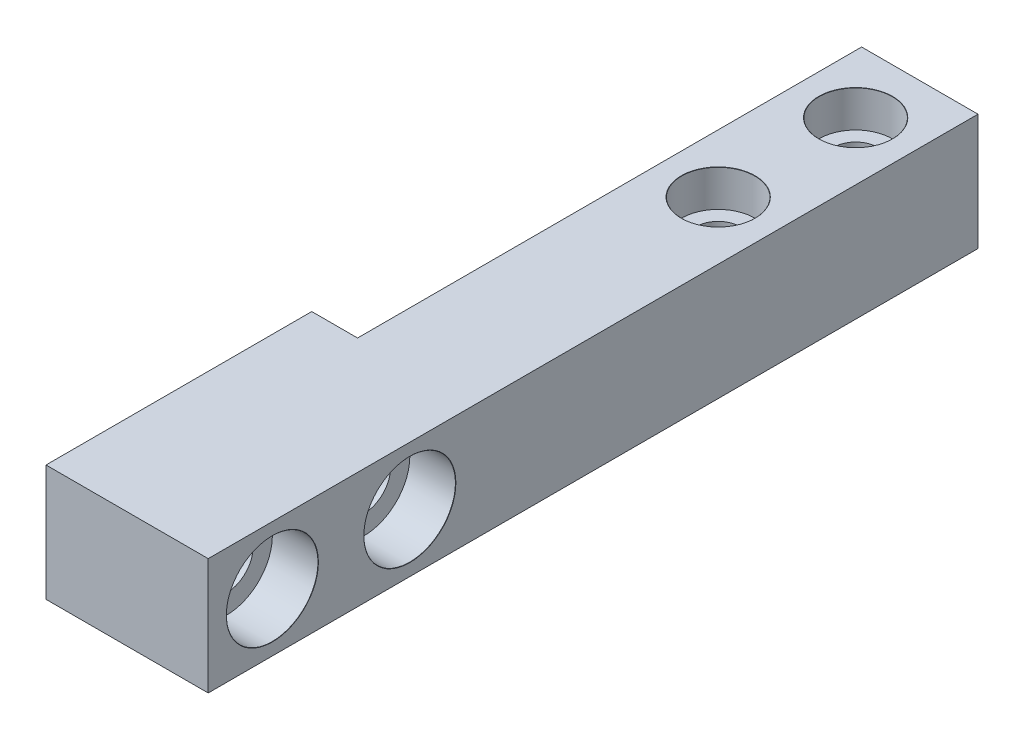
SolidWorks part; units mm, degrees
ref_plane "Front Plane" through (0, 0, 0) normal (0, 0, 1) x (1, 0, 0)
ref_plane "Top Plane" through (0, 0, 0) normal (0, 1, 0) x (1, 0, 0)
ref_plane "Right Plane" through (0, 0, 0) normal (1, 0, 0) x (0, 0, -1)
sketch "Sketch2" plane through (0, 0, 0) normal (0, 1, 0) x (1, 0, 0)
  line L1 (-6.35, -42) -> (6.35, -42)
  line L2 (-6.35, -42) -> (-6.35, 42)
  line L3 (-6.35, 42) -> (6.35, 42)
  line L4 (6.35, -42) -> (6.35, 42)
  line L5 (-6.35, -42) -> (6.35, 42) construction
  line L6 (-6.35, 42) -> (6.35, -42) construction
  point P0 (0, 0)
  dimension "D1" = 84
  dimension "D2" = 12.7
extrude "Boss-Extrude1" add sketch "Sketch2" along normal blind 12.7
hole_wizard "CBORE for M4 SHCS1" positions "Sketch3" profile "Sketch4" counterbore size "M4" standard "ANSI Metric" end condition through all
sketch "Sketch3" plane through (0, 12.7, 0) normal (0, -1, 0) x (-1, 0, 0)
  line L0 (0, 35) -> (0, 20) construction
  line L1 (0, -20) -> (0, -35) construction
  line L2 (0, 20) -> (0, -20) construction
  circle A0 centre (0, -20) radius 2.5 construction
  circle A1 centre (0, -35) radius 2.5 construction
  point P0 (0, 35)
  point P2 (0, 20)
  point P28 (0, 0)
  dimension "D2" = 5
  dimension "D1" = 15
  dimension "D3" = 15
  dimension "D4" = 40
sketch "Sketch4" plane through (0, 12.7, -35) normal (1, 0, 0) x (0, 0, 1)
  line L0 (0, 0) -> (0, 12.7)
  line L1 (0, 12.7) -> (2.4, 12.7)
  line L3 (2.4, 12.7) -> (2.4, 4)
  line L4 (4, 4) -> (2.4, 4)
  line L5 (4, 4) -> (4, 0.021)
  line L6 (4, 0.021) -> (4.025, 0)
  line L7 (4.025, 0) -> (0, 0)
  line L8 (-4, 0.021) -> (-4.025, 0) construction
  line L11 (0, -6.35) -> (0, 107.95) construction
  dimension "Thru Hole Dia." = 4.8
  dimension "Thru Hole Depth" = 12.7
  dimension "C'Bore Dia." = 8
  dimension "C'Bore Depth" = 4
  dimension "Near C'Sink Dia." = 8.05
  dimension "Near C'Sink Angle" = 100
sketch "Sketch8" plane through (-6.35, 0, 0) normal (-1, 0, 0) x (0, 0, 1)
  line L0 (-42, 0) -> (42, 0) construction
  line L1 (42, 12.7) -> (13, 12.7)
  line L2 (42, 12.7) -> (42, 0)
  line L3 (42, 0) -> (13, 0)
  line L4 (13, 12.7) -> (13, 0)
  dimension "D1" = 29
extrude "Boss-Extrude3" add sketch "Sketch8" along normal blind 5
hole_wizard "CBORE for M5 SHCS2" positions "Sketch6" profile "Sketch7" counterbore size "M5" standard "ANSI Metric" end condition through all
sketch "Sketch6" plane through (6.35, 0, 0) normal (1, 0, 0) x (0, 0, -1)
  line L0 (-35, 6.35) -> (-20, 6.35) construction
  line L2 (20, 6.35) -> (35, 6.35) construction
  line L4 (-20, 6.35) -> (20, 6.35) construction
  line L6 (-42, 12.7) -> (-42, 0) construction
  circle A0 centre (20, 6.35) radius 2.5 construction
  circle A1 centre (35, 6.35) radius 2.5 construction
  point P0 (-35, 6.35)
  point P2 (-20, 6.35)
  point P26 (0, 6.35)
  point P29 (-42, 6.35)
  dimension "D1" = 5
  dimension "D2" = 15
  dimension "D3" = 15
  dimension "D4" = 40
sketch "Sketch7" plane through (6.35, 6.35, 35) normal (0, 1, 0) x (0, 0, -1)
  line L0 (0, 0) -> (0, 17.7)
  line L1 (0, 17.7) -> (2.9, 17.7)
  line L3 (2.9, 17.7) -> (2.9, 5)
  line L4 (5, 5) -> (2.9, 5)
  line L5 (5, 5) -> (5, 0.021)
  line L6 (5, 0.021) -> (5.025, 0)
  line L7 (5.025, 0) -> (0, 0)
  line L8 (-5, 0.021) -> (-5.025, 0) construction
  line L11 (0, -6.35) -> (0, 107.95) construction
  dimension "Thru Hole Dia." = 5.8
  dimension "Thru Hole Depth" = 17.7
  dimension "C'Bore Dia." = 10
  dimension "C'Bore Depth" = 5
  dimension "Near C'Sink Dia." = 10.05
  dimension "Near C'Sink Angle" = 100
sketch "Sketch9" plane through (0, 12.7, 0) normal (0, 1, 0) x (1, 0, 0)
  line L0 (0, 35) -> (0, 20) construction
  point P4 (0, 27.5)
